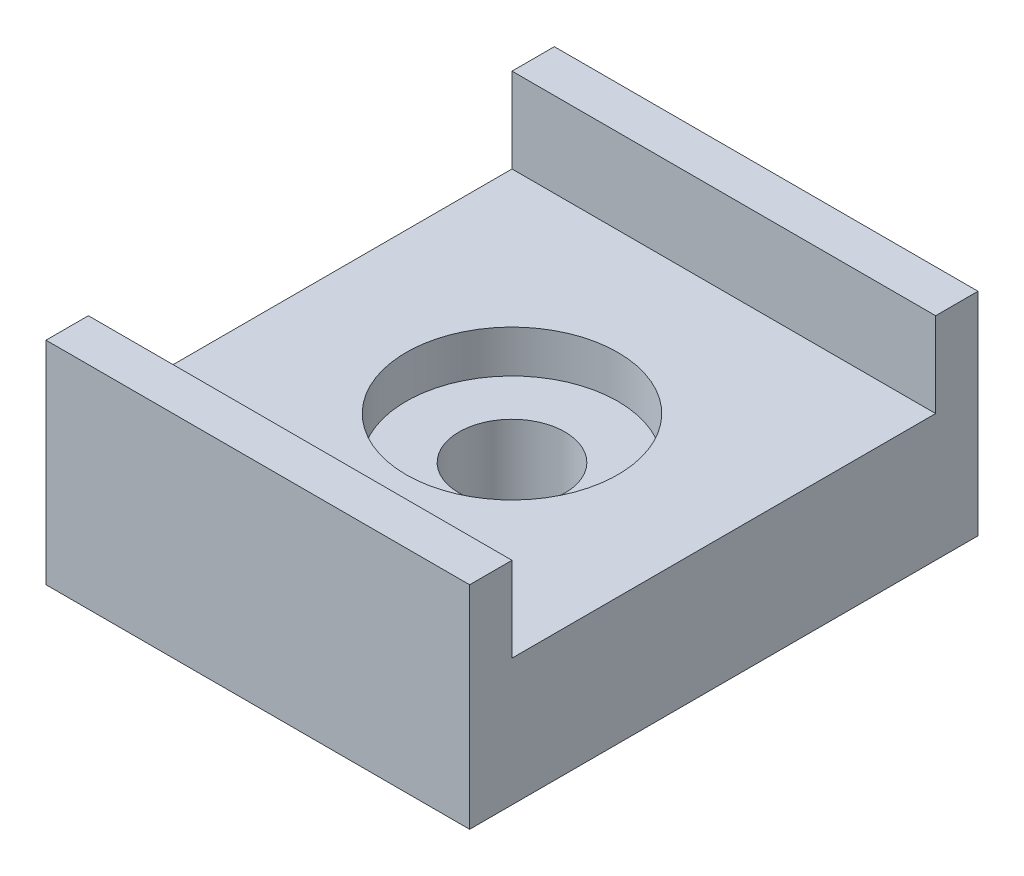
SolidWorks part; units mm, degrees
ref_plane "Front Plane" through (0, 0, 0) normal (0, 0, 1) x (1, 0, 0)
ref_plane "Top Plane" through (0, 0, 0) normal (0, 1, 0) x (1, 0, 0)
ref_plane "Right Plane" through (0, 0, 0) normal (1, 0, 0) x (0, 0, -1)
sketch "Sketch1" plane through (0, 0, 0) normal (1, 0, 0) x (0, 0, -1)
  line L0 (27.94, 12.7) -> (30.48, 12.7)
  line L1 (0, 0) -> (30.48, 0)
  line L2 (0, 0) -> (0, 12.7)
  line L3 (0, 12.7) -> (2.54, 12.7)
  line L4 (30.48, 0) -> (30.48, 12.7)
  line L6 (2.54, 12.7) -> (2.54, 7.62)
  line L7 (2.54, 7.62) -> (27.94, 7.62)
  line L8 (27.94, 12.7) -> (27.94, 7.62)
  point P9 (27.8606, 33.1391)
  point P10 (15.24, 7.62)
  point P11 (15.24, 0)
  dimension "D1" = 30.48
  dimension "D2" = 12.7
  dimension "D3" = 25.4
  dimension "D5" = 7.62
extrude "Boss-Extrude1" add sketch "Sketch1" along normal blind 25.4
sketch "Sketch2" plane through (0, 7.62, 0) normal (0, 1, 0) x (1, 0, 0)
  line L0 (0, 15.24) -> (25.4, 15.24) construction
  line L1 (0, 27.94) -> (0, 2.54) construction
  line L2 (25.4, 27.94) -> (25.4, 2.54) construction
  line L3 (12.7, 0) -> (12.7, 30.48) construction
  line L4 (25.4, 0) -> (0, 0) construction
  line L5 (25.4, 30.48) -> (0, 30.48) construction
  circle A0 centre (12.7, 15.24) radius 3.175
  point P14 (12.7, 15.24)
  dimension "D1" = 6.35
extrude "Cut-Extrude1" cut sketch "Sketch2" against normal through all
sketch "Sketch3" plane through (0, 7.62, 0) normal (0, 1, 0) x (1, 0, 0)
  circle A0 centre (12.7, 15.24) radius 6.35
  point P3 (12.7, 15.24)
  dimension "D1" = 12.7
extrude "Cut-Extrude2" cut sketch "Sketch3" against normal blind 2.54
